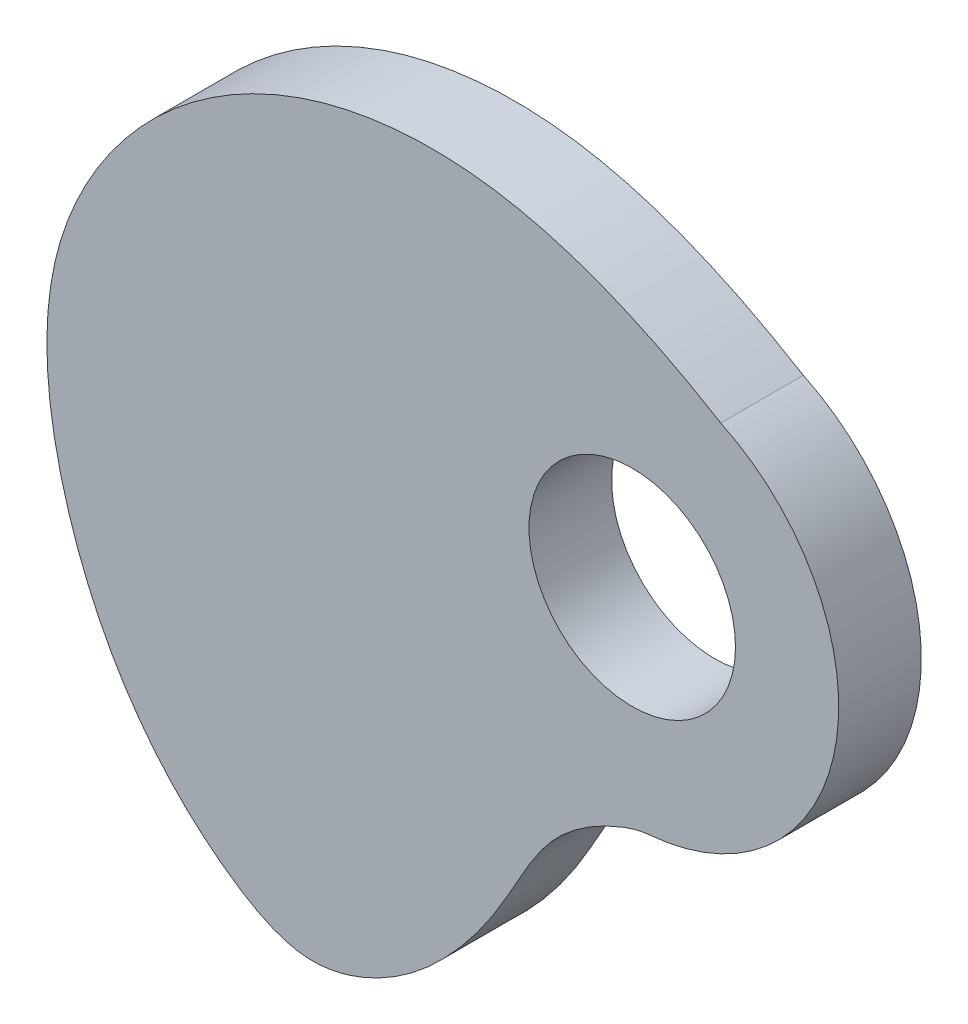
SolidWorks part; units mm, degrees
ref_plane "Front Plane" through (0, 0, 0) normal (0, 0, 1) x (1, 0, 0)
ref_plane "Top Plane" through (0, 0, 0) normal (0, 1, 0) x (1, 0, 0)
ref_plane "Right Plane" through (0, 0, 0) normal (1, 0, 0) x (0, 0, -1)
sketch "Sketch1" plane through (0, 0, 0) normal (0, 0, 1) x (1, 0, 0)
  line L0 (0, 80) -> (180, 80) construction
  line L1 (180, 80) -> (180, 130) construction
  line L2 (180, 130) -> (0, 130) construction
  line L3 (0, 130) -> (0, 80) construction
  line L4 (60, 130) -> (60, 80) construction
  line L5 (75, 130) -> (75, 80) construction
  line L6 (105, 130) -> (105, 80) construction
  line L7 (10, 130) -> (10, 80) construction
  line L8 (20, 130) -> (20, 80) construction
  line L9 (30, 130) -> (30, 80) construction
  line L10 (40, 130) -> (40, 80) construction
  line L11 (50, 130) -> (50, 80) construction
  line L12 (80, 130) -> (80, 80) construction
  line L13 (85, 130) -> (85, 80) construction
  line L14 (90, 130) -> (90, 80) construction
  line L15 (95, 130) -> (95, 80) construction
  line L16 (100, 130) -> (100, 80) construction
  line L17 (0, 105) -> (-12.5, 126.6506) construction
  line L18 (0, 105) -> (-21.6506, 117.5) construction
  line L19 (-25, 105) -> (30, 105) construction
  line L20 (0, 105) -> (-21.6506, 92.5) construction
  line L21 (0, 105) -> (-12.5, 83.3494) construction
  line L22 (-12.5, 126.6506) -> (50, 126.6506) construction
  line L23 (-21.6506, 117.5) -> (40, 117.5) construction
  line L24 (-21.6506, 92.5) -> (20, 92.5) construction
  line L25 (-12.5, 83.3494) -> (10, 83.3494) construction
  line L26 (60, 130) -> (75, 130)
  line L27 (75, 83.3494) -> (100, 83.3494) construction
  line L28 (75, 92.5) -> (95, 92.5) construction
  line L29 (75, 117.5) -> (85, 117.5) construction
  line L30 (75, 126.6506) -> (80, 126.6506) construction
  line L31 (75, 105) -> (90, 105) construction
  arc A0 (0, 80) -> (0, 130) centre (0, 105) cw
  spline S0 degree 3 poles (0, 80) (8.6338, 80.5841) (18.6781, 90.2211) (30, 105) (41.3219, 119.7789) (51.3662, 129.4159) (60, 130) knots 0 0 0 0 0.300445 0.5 0.699555 1 1 1 1
  spline S1 degree 3 poles (75, 130) (80.662, 128.024) (84.7223, 118.3047) (90, 105) (95.2777, 91.6953) (99.338, 81.976) (105, 80) knots 0 0 0 0 0.274933 0.5 0.725067 1 1 1 1
  dimension "D1" = 80
  dimension "D2" = 50
  dimension "D3" = 60
  dimension "D4" = 15
  dimension "D5" = 30
  dimension "D6" = 75
  dimension "D7" = 10
  dimension "D8" = 5
  dimension "D9" = 5
  dimension "D11" = 30
  dimension "D12" = 30
  dimension "D13" = 30
  dimension "D14" = 30
  dimension "D10" = 5
sketch "Sketch2" plane through (0, 0, 0) normal (0, 0, 1) x (1, 0, 0)
  line L0 (15, 0) -> (15, 31.6228) construction
  line L1 (15, 31.6228) -> (0, 0) construction
  line L2 (0, 0) -> (-34.8861, -2.821) construction
  line L3 (0, 0) -> (-28.8018, -19.8861) construction
  line L4 (0, 0) -> (2.821, -34.8861) construction
  line L5 (0, 0) -> (3.2798, 34.846) construction
  line L6 (0, 0) -> (-20.2634, -28.5376) construction
  line L7 (0, 0) -> (-33.7471, 9.2809) construction
  line L8 (0, 0) -> (-28.5376, 20.2634) construction
  line L9 (0, 0) -> (-19.8861, 28.8018) construction
  line L10 (0, 0) -> (-8.8361, 33.8663) construction
  line L11 (0, 0) -> (-24.911, -24.5854) construction
  line L12 (0, 0) -> (-15, -31.6228) construction
  line L13 (0, 0) -> (-9.2809, -33.7471) construction
  line L14 (0, 0) -> (-3.2798, -34.846) construction
  line L15 (0, 0) -> (-24.911, -24.5854) construction
  line L16 (0, 0) -> (-20.2634, -28.5376) construction
  circle A0 centre (0, 0) radius 25 construction
  circle A1 centre (0, 0) radius 15 construction
  circle A2 centre (0, 0) radius 35 construction
  circle A3 centre (15, 31.6228) radius 10
  point P20 (0, 0)
  dimension "D1" = 50
  dimension "D2" = 30
  dimension "D3" = 70
  dimension "D4" = 120
  dimension "D5" = 30
  dimension "D6" = 60
  dimension "D7" = 20
  dimension "D9" = 10
  dimension "D10" = 5
  dimension "D11" = 10
  dimension "D8" = 5
sketch "Sketch7" plane through (0, 0, 0) normal (0, 0, 1) x (1, 0, 0)
  line L0 (10, 83.3494) -> (10, 80) construction
  line L1 (0, 80) -> (180, 80) construction
  line L2 (30, 105) -> (30, 80) construction
  line L3 (40, 117.5) -> (40, 80) construction
  line L4 (50, 126.6506) -> (50, 80) construction
  line L5 (60, 130) -> (60, 80) construction
  line L6 (20, 92.5) -> (20, 80) construction
  line L7 (75, 130) -> (75, 80) construction
  line L8 (100, 83.3494) -> (100, 80) construction
  line L9 (95, 92.5) -> (95, 80) construction
  line L10 (90, 105) -> (90, 80) construction
  line L11 (85, 117.5) -> (85, 80) construction
  line L12 (80, 126.6506) -> (80, 80) construction
sketch "Sketch9" plane through (0, 0, 0) normal (0, 0, 1) x (1, 0, 0)
sketch "Sketch10" plane through (0, 0, 0) normal (0, 0, 1) x (1, 0, 0)
sketch "Sketch11" plane through (0, 0, 0) normal (0, 0, 1) x (1, 0, 0)
sketch "Sketch12" plane through (0, 0, 0) normal (0, 0, 1) x (1, 0, 0)
sketch "Sketch14" plane through (0, 0, 0) normal (0, 0, 1) x (1, 0, 0)
  line L0 (3.2798, 34.846) -> (14.1139, 5.0793) construction
  line L1 (-8.8361, 33.8663) -> (11.4907, 9.6418) construction
  line L2 (-19.8861, 28.8018) -> (7.5, 12.9904) construction
  circle A0 centre (0, 0) radius 15 construction
sketch "Sketch15" plane through (0, 0, 0) normal (0, 0, 1) x (1, 0, 0)
  line L0 (3.2798, 34.846) -> (2.1743, 38.0083) construction
  line L1 (-28.5376, 20.2634) -> (2.6047, 14.7721) construction
  line L2 (-33.7471, 9.2809) -> (-2.6049, 14.7721) construction
  line L3 (-34.8861, -2.821) -> (-7.4752, 13.0047) construction
  line L4 (-28.8018, -19.8861) -> (-12.9904, 7.5) construction
  line L5 (-24.911, -24.5854) -> (-14.0954, 5.1303) construction
  line L6 (-20.2634, -28.5376) -> (-14.7721, 2.6047) construction
  line L7 (-15, -31.6228) -> (-15, 0) construction
  line L8 (-9.2809, -33.7471) -> (-14.7721, -2.6049) construction
  line L9 (-3.2798, -34.846) -> (-14.0768, -5.1812) construction
  line L11 (-8.8361, 33.8663) -> (-16.8709, 43.4418) construction
  line L12 (-19.8861, 28.8018) -> (-41.5368, 41.3018) construction
  line L13 (-28.5376, 20.2634) -> (-65.4679, 26.7752) construction
  line L14 (-33.7471, 9.2809) -> (-79.6884, 1.1802) construction
  line L15 (-34.8861, -2.821) -> (-78.1874, -27.821) construction
  line L16 (-28.8018, -19.8861) -> (-53.8018, -63.1874) construction
  line L17 (-24.911, -24.5854) -> (-40.8663, -68.422) construction
  line L18 (-20.2634, -28.5376) -> (-26.7752, -65.4679) construction
  line L19 (-15, -31.6228) -> (-15, -56.6228) construction
  line L20 (-9.2809, -33.7471) -> (-7.1103, -46.0572) construction
  line L21 (-3.2798, -34.846) -> (-2.134, -37.994) construction
  circle A0 centre (0, 0) radius 15 construction
  dimension "D1" = 3.35
  dimension "D2" = 12.5
  dimension "D3" = 25
  dimension "D4" = 37.5
  dimension "D5" = 46.65
  dimension "D6" = 50
  dimension "D7" = 50
  dimension "D8" = 46.65
  dimension "D9" = 37.5
  dimension "D10" = 25
  dimension "D11" = 12.5
  dimension "D12" = 3.35
sketch "Sketch16" plane through (0, 0, 0) normal (0, 0, 1) x (1, 0, 0)
sketch "Sketch17" plane through (0, 0, 0) normal (0, 0, 1) x (1, 0, 0)
  circle A0 centre (2.1743, 38.0083) radius 9.8051
  circle A1 centre (-16.8709, 43.4418) radius 10
  circle A2 centre (-41.5368, 41.3018) radius 10
  circle A3 centre (-65.4679, 26.7752) radius 10
  circle A4 centre (-79.6884, 1.1802) radius 10
  circle A5 centre (-78.1874, -27.821) radius 10
  circle A6 centre (-53.8018, -63.1874) radius 10
  circle A7 centre (-40.8663, -68.422) radius 10
  circle A8 centre (-26.7752, -65.4679) radius 10
  circle A9 centre (-15, -56.6228) radius 10
  circle A10 centre (-7.1103, -46.0572) radius 10
  circle A11 centre (2.821, -34.8861) radius 10
sketch "Sketch18" plane through (0, 0, 0) normal (0, 0, 1) x (1, 0, 0)
  circle A0 centre (-2.134, -37.994) radius 10
sketch "CAM Profile" plane through (0, 0, 0) normal (0, 0, 1) x (1, 0, 0)
  line L0 (0, 0) -> (2.821, -34.8861) construction
  arc A0 (2.015, -24.9187) -> (10.7143, 22.5877) centre (0, 0) ccw
  circle A1 centre (2.821, -34.8861) radius 10 construction
  circle A2 centre (15, 31.6228) radius 10 construction
  circle A3 centre (2.1743, 38.0083) radius 9.8051 construction
  circle A4 centre (-16.8709, 43.4418) radius 10 construction
  circle A5 centre (-41.5368, 41.3018) radius 10 construction
  circle A6 centre (-65.4679, 26.7752) radius 10 construction
  circle A7 centre (-79.6884, 1.1802) radius 10 construction
  circle A8 centre (-78.1874, -27.821) radius 10 construction
  circle A9 centre (-53.8018, -63.1874) radius 10 construction
  circle A10 centre (-40.8663, -68.422) radius 10 construction
  circle A11 centre (-26.7752, -65.4679) radius 10 construction
  circle A12 centre (-15, -56.6228) radius 10 construction
  circle A13 centre (-7.1103, -46.0572) radius 10 construction
  circle A14 centre (-2.134, -37.994) radius 10 construction
  spline S0 degree 3 poles (10.7143, 22.5877) (1.9768, 27.8889) (-14.2914, 35.1888) (-39.9088, 33.1444) (-59.8923, 21.093) (-72.4811, -0.6403) (-69.6241, -29.6113) (-56.7882, -50.6646) (-39.7846, -59.7962) (-29.7719, -56.5749) (-21.8151, -49.8937) (-15.2997, -41.0122) (-10.6898, -31.0056) (-3.4134, -26.3747) (0.8528, -25.0126) (2.015, -24.9187) knots 0 0 0 0 0.138432 0.230574 0.333853 0.440156 0.547941 0.709692 0.750139 0.793813 0.839921 0.88898 0.94079 0.984264 1 1 1 1
sketch "Sketch23" plane through (0, 0, 0) normal (0, 0, 1) x (1, 0, 0)
  circle A0 centre (0, 0) radius 12.5
sketch "Roller Profile" plane through (0, 0, 0) normal (0, 0, 1) x (1, 0, 0)
  line L0 (9, 31.6228) -> (9, 81.6228)
  line L1 (9, 81.6228) -> (21, 81.6228)
  line L2 (21, 81.6228) -> (21, 31.6228)
  circle A0 centre (15, 31.6228) radius 2.5
  arc A1 (9, 31.6228) -> (21, 31.6228) centre (15, 31.6228) ccw
  circle A2 centre (15, 31.6228) radius 10
  dimension "D1" = 50
  dimension "D2" = 12
extrude "Boss-Extrude3" add sketch "CAM Profile" along normal mid plane 10 contours S0 A0
extrude "Cut-Extrude2" cut sketch "Sketch23" against normal mid plane 10 contours A0
